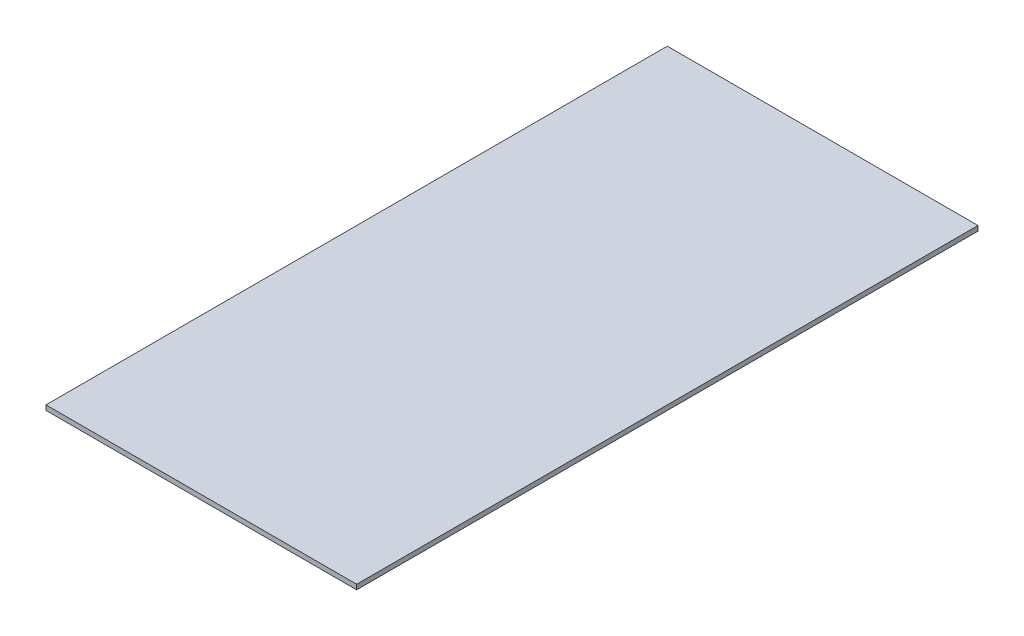
SolidWorks part; units mm, degrees
ref_plane "Front Plane" through (0, 0, 0) normal (0, 0, 1) x (1, 0, 0)
ref_plane "Top Plane" through (0, 0, 0) normal (0, 1, 0) x (1, 0, 0)
ref_plane "Right Plane" through (0, 0, 0) normal (1, 0, 0) x (0, 0, -1)
sketch "Sketch1" plane through (0, 0, 0) normal (0, 1, 0) x (1, 0, 0)
  line L1 (-609.6, -1219.2) -> (609.6, -1219.2)
  line L2 (-609.6, -1219.2) -> (-609.6, 1219.2)
  line L3 (-609.6, 1219.2) -> (609.6, 1219.2)
  line L4 (609.6, -1219.2) -> (609.6, 1219.2)
  line L5 (-609.6, -1219.2) -> (609.6, 1219.2) construction
  line L6 (-609.6, 1219.2) -> (609.6, -1219.2) construction
  point P0 (0, 0)
  dimension "D1" = 2438.4
  dimension "D2" = 1219.2
extrude "Boss-Extrude1" add sketch "Sketch1" along normal blind 19.05
